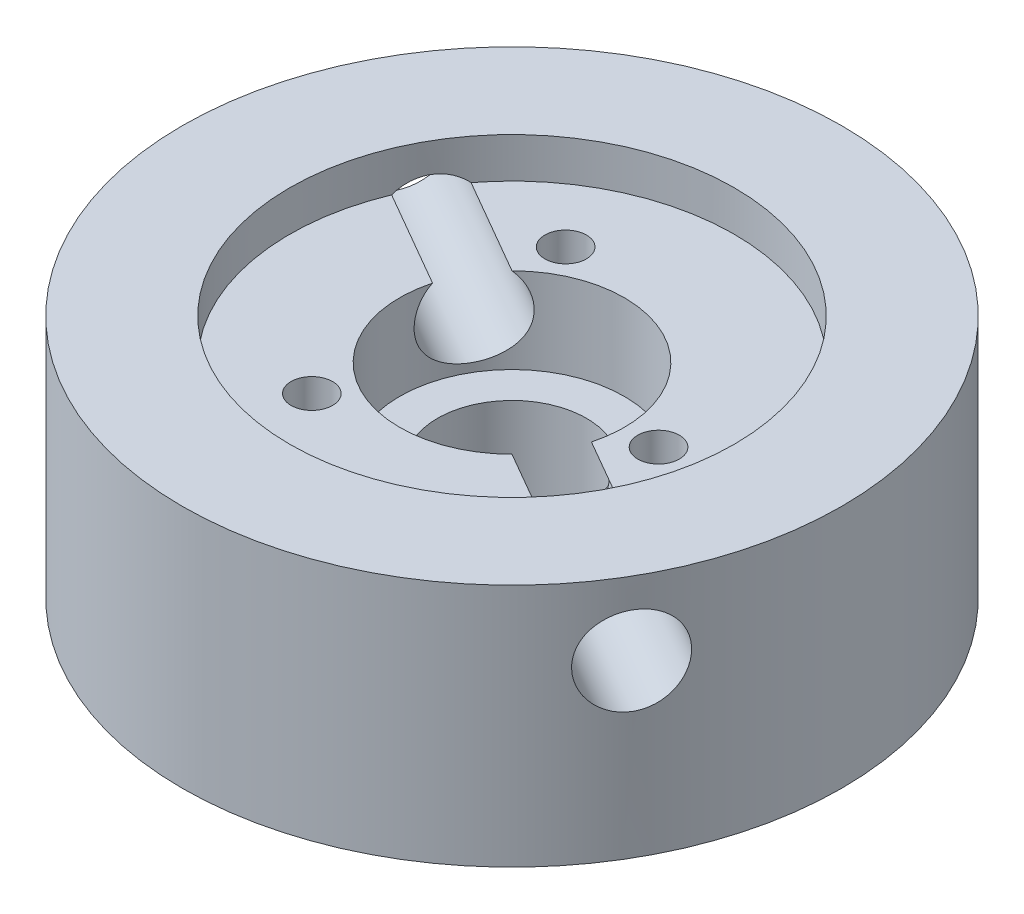
SolidWorks part; units mm, degrees
other "Printed Wheel Rim"
ref_plane "Front Plane" through (0, 0, 0) normal (0, 0, 1) x (1, 0, 0)
ref_plane "Top Plane" through (0, 0, 0) normal (0, 1, 0) x (1, 0, 0)
ref_plane "Right Plane" through (0, 0, 0) normal (1, 0, 0) x (0, 0, -1)
sketch3d "Tyre seat blank sketch datum points"
  point P0 (-19.0092, -283, -53.2449)
  point P1 (-9.0092, -283, -53.2449)
  point P2 (-19.0092, -283, -63.2449)
ref_plane "Tyre seat blank sketch plane" through (0, -283, 0) normal (0, 1, 0) x (1, 0, 0)
sketch "Tyre seat blank sketch" plane through (0, -283, 0) normal (0, 1, 0) x (1, 0, 0)
  circle A0 centre (-19.0092, 53.2449) radius 27
extrude "Tyre seat blank" add sketch "Tyre seat blank sketch" along normal blind 20 separate body
sketch3d "Axle clearance sketch datum points"
  point P0 (-19.0092, -283.1, -53.2449)
  point P1 (-9.0092, -283.1, -53.2449)
  point P2 (-19.0092, -283.1, -63.2449)
ref_plane "Axle clearance sketch plane" through (0, -283.1, 0) normal (0, 1, 0) x (1, 0, 0)
sketch "Axle clearance sketch" plane through (0, -283.1, 0) normal (0, 1, 0) x (1, 0, 0)
  circle A0 centre (-19.0092, 53.2449) radius 6.1
extrude "Axle clearance" cut sketch "Axle clearance sketch" along normal blind 20.2
sketch3d "Hub neck socket sketch datum points"
  point P0 (-19.0092, -273.3, -53.2449)
  point P1 (-9.0092, -273.3, -53.2449)
  point P2 (-19.0092, -273.3, -63.2449)
ref_plane "Hub neck socket sketch plane" through (0, -273.3, 0) normal (0, 1, 0) x (1, 0, 0)
sketch "Hub neck socket sketch" plane through (0, -273.3, 0) normal (0, 1, 0) x (1, 0, 0)
  circle A0 centre (-19.0092, 53.2449) radius 9.2
extrude "Hub neck socket" cut sketch "Hub neck socket sketch" along normal blind 10.5
sketch3d "Hub flange socket sketch datum points"
  point P0 (-19.0092, -266.3, -53.2449)
  point P1 (-9.0092, -266.3, -53.2449)
  point P2 (-19.0092, -266.3, -63.2449)
ref_plane "Hub flange socket sketch plane" through (0, -266.3, 0) normal (0, 1, 0) x (1, 0, 0)
sketch "Hub flange socket sketch" plane through (0, -266.3, 0) normal (0, 1, 0) x (1, 0, 0)
  circle A0 centre (-19.0092, 53.2449) radius 18.2
extrude "Hub flange socket" cut sketch "Hub flange socket sketch" along normal blind 3.5
sketch3d "Rim bolt pattern sketch datum points"
  point P0 (-19.0092, -283.1, -53.2449)
  point P1 (-9.0092, -283.1, -53.2449)
  point P2 (-19.0092, -283.1, -63.2449)
ref_plane "Rim bolt pattern sketch plane" through (0, -283.1, 0) normal (0, 1, 0) x (1, 0, 0)
sketch "Rim bolt pattern sketch" plane through (0, -283.1, 0) normal (0, 1, 0) x (1, 0, 0)
  circle A0 centre (-7.0092, 53.2449) radius 1.7
  circle A1 centre (-25.0092, 42.8526) radius 1.7
  circle A2 centre (-25.0092, 63.6372) radius 1.7
extrude "Rim bolt pattern" cut sketch "Rim bolt pattern sketch" along normal blind 20.2
sketch3d "Rim nut pockets sketch datum points"
  point P0 (-19.0092, -283.1, -53.2449)
  point P1 (-9.0092, -283.1, -53.2449)
  point P2 (-19.0092, -283.1, -63.2449)
ref_plane "Rim nut pockets sketch plane" through (0, -283.1, 0) normal (0, 1, 0) x (1, 0, 0)
sketch "Rim nut pockets sketch" plane through (0, -283.1, 0) normal (0, 1, 0) x (1, 0, 0)
  line L0 (-3.7092, 53.2449) -> (-5.3592, 56.1028)
  line L1 (-5.3592, 56.1028) -> (-8.6592, 56.1028)
  line L2 (-8.6592, 56.1028) -> (-10.3092, 53.2449)
  line L3 (-10.3092, 53.2449) -> (-8.6592, 50.387)
  line L4 (-8.6592, 50.387) -> (-5.3592, 50.387)
  line L5 (-5.3592, 50.387) -> (-3.7092, 53.2449)
  line L6 (-21.7092, 42.8526) -> (-23.3592, 45.7105)
  line L7 (-23.3592, 45.7105) -> (-26.6592, 45.7105)
  line L8 (-26.6592, 45.7105) -> (-28.3092, 42.8526)
  line L9 (-28.3092, 42.8526) -> (-26.6592, 39.9947)
  line L10 (-26.6592, 39.9947) -> (-23.3592, 39.9947)
  line L11 (-23.3592, 39.9947) -> (-21.7092, 42.8526)
  line L12 (-21.7092, 63.6372) -> (-23.3592, 66.4951)
  line L13 (-23.3592, 66.4951) -> (-26.6592, 66.4951)
  line L14 (-26.6592, 66.4951) -> (-28.3092, 63.6372)
  line L15 (-28.3092, 63.6372) -> (-26.6592, 60.7793)
  line L16 (-26.6592, 60.7793) -> (-23.3592, 60.7793)
  line L17 (-23.3592, 60.7793) -> (-21.7092, 63.6372)
  circle A0 centre (-7.0092, 53.2449) radius 3.3 construction
  circle A1 centre (-25.0092, 42.8526) radius 3.3 construction
  circle A2 centre (-25.0092, 63.6372) radius 3.3 construction
extrude "Rim nut pockets" cut sketch "Rim nut pockets sketch" along normal blind 2.7
sketch3d "Hub pin service window sketch datum points"
  point P0 (-43.2579, -269, -67.2449)
  point P1 (-38.2579, -269, -75.9051)
  point P2 (-43.2579, -259, -67.2449)
ref_plane "Hub pin service window sketch plane" through (-61.5613, 0, -35.5424) normal (0.866, 0, 0.5) x (0.5, 0, -0.866)
sketch "Hub pin service window sketch" plane through (-61.5613, 0, -35.5424) normal (0.866, 0, 0.5) x (0.5, 0, -0.866)
  circle A0 centre (36.6068, -269) radius 3.6
extrude "Hub pin service window" cut sketch "Hub pin service window sketch" along normal blind 56
